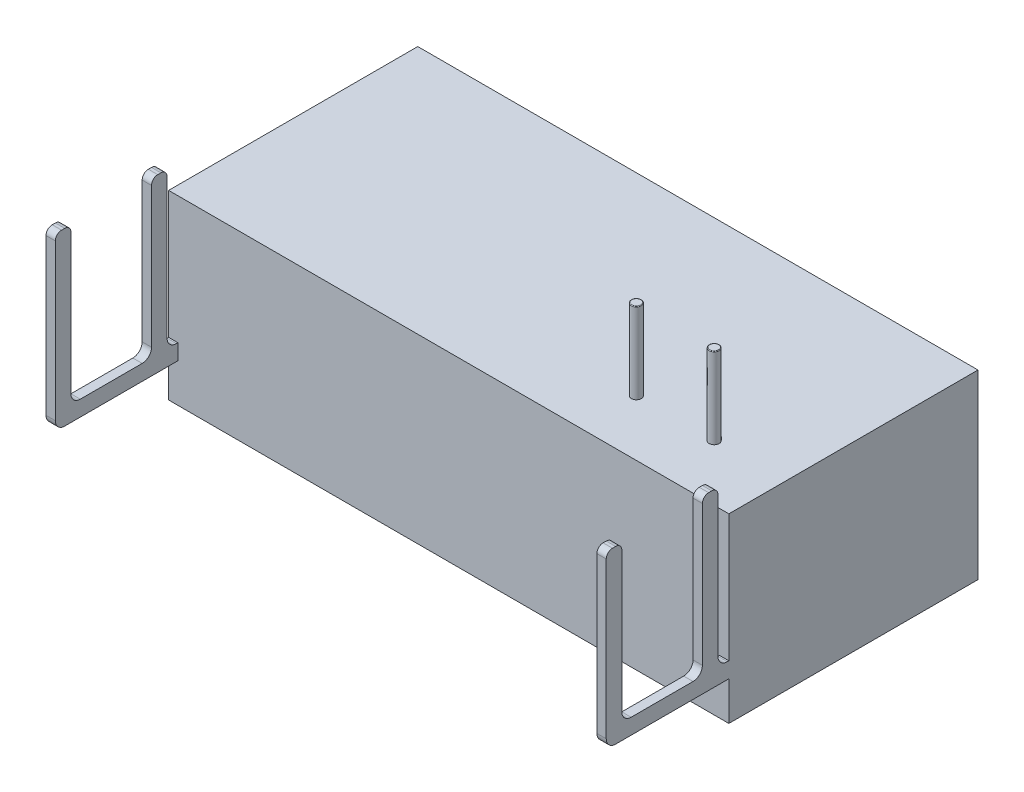
SolidWorks part; units mm, degrees
ref_plane "Front Plane" through (0, 0, 0) normal (0, 0, 1) x (1, 0, 0)
ref_plane "Top Plane" through (0, 0, 0) normal (0, 1, 0) x (1, 0, 0)
ref_plane "Right Plane" through (0, 0, 0) normal (1, 0, 0) x (0, 0, -1)
sketch "Sketch1" plane through (0, 0, 0) normal (1, 0, 0) x (0, 0, -1)
  line L1 (0, 0) -> (800, 0)
  line L2 (0, 0) -> (0, 583)
  line L3 (0, 583) -> (800, 583)
  line L4 (800, 0) -> (800, 583)
  dimension "D1" = 800
  dimension "D2" = 583
extrude "Boss-Extrude1" add sketch "Sketch1" along normal blind 1798.93
sketch "Sketch2" plane through (0, 583, 0) normal (0, 1, 0) x (1, 0, 0)
  line L0 (1798.93, 800) -> (1798.93, 0) construction
  circle A0 centre (1572.09, 179.8) radius 16
  dimension "D1" = 32
  dimension "D2" = 226.84
extrude "Boss-Extrude2" add sketch "Sketch2" along normal blind 260
pattern_linear "LPattern1" count 2 spacing 250 along (-1, 0, 0) of "Boss-Extrude2"
sketch "Sketch3" plane through (0, 0, 0) normal (-1, 0, 0) x (0, 0, 1)
  line L0 (0, 174.273) -> (5, 174.273)
  line L1 (0, 583) -> (0, 0) construction
  line L2 (343.77, 204.273) -> (343.77, 654.273)
  line L3 (363.77, 674.273) -> (373.77, 674.273)
  line L4 (393.77, 654.273) -> (393.77, 154.273)
  line L5 (363.77, 124.273) -> (0, 124.273)
  line L6 (0, 174.273) -> (0, 124.273)
  line L7 (35, 204.273) -> (35, 654.273)
  line L8 (55, 674.273) -> (65, 674.273)
  line L9 (85, 654.273) -> (85, 204.273)
  line L10 (115, 174.273) -> (313.77, 174.273)
  arc A0 (393.77, 654.273) -> (373.77, 674.273) centre (373.77, 654.273) ccw
  arc A1 (343.77, 654.273) -> (363.77, 674.273) centre (363.77, 654.273) cw
  arc A2 (363.77, 124.273) -> (393.77, 154.273) centre (363.77, 154.273) ccw
  arc A3 (313.77, 174.273) -> (343.77, 204.273) centre (313.77, 204.273) ccw
  arc A4 (65, 674.273) -> (85, 654.273) centre (65, 654.273) cw
  arc A5 (35, 654.273) -> (55, 674.273) centre (55, 654.273) cw
  arc A6 (85, 204.273) -> (115, 174.273) centre (115, 204.273) ccw
  arc A7 (5, 174.273) -> (35, 204.273) centre (5, 204.273) ccw
  point P4 (368.77, 674.273)
  dimension "D5" = 20
  dimension "D6" = 30
  dimension "D9" = 20
  dimension "D10" = 30
  dimension "D1" = 50
  dimension "D2" = 50
  dimension "D3" = 550
  dimension "D4" = 393.77
  dimension "D7" = 85
  dimension "D8" = 50
extrude "Boss-Extrude4" add sketch "Sketch3" against normal blind 30
pattern_linear "LPattern3" count 2 spacing 1768.93 along (1, 0, 0) of "Boss-Extrude4"
fillet "Fillet1" radius 2 2 edges at (1572.09, 843, -163.8) (1322.09, 843, -163.8)
